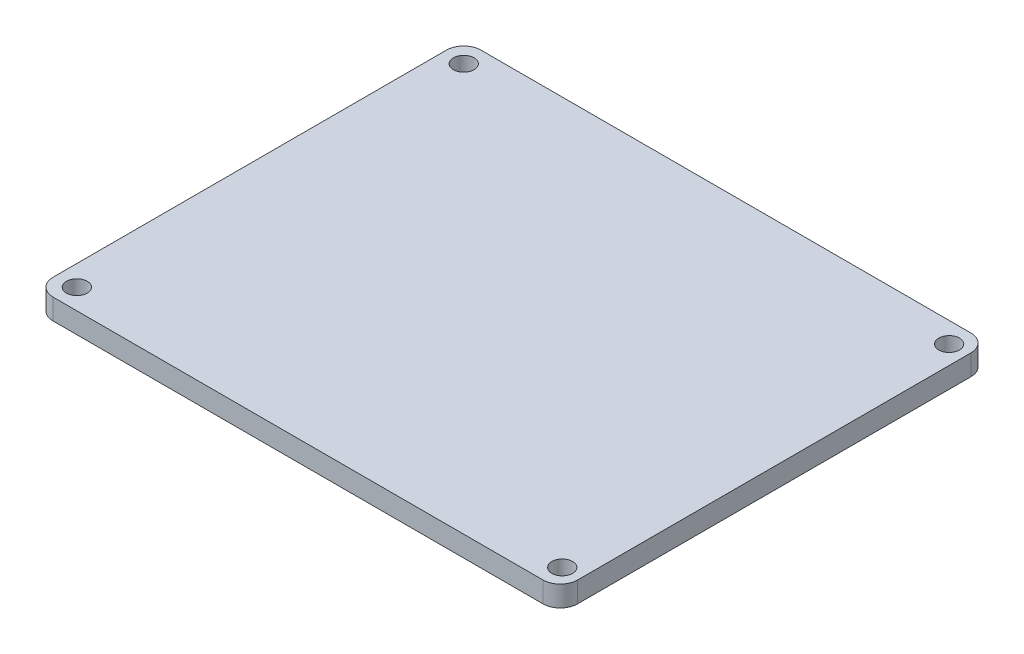
SolidWorks part; units mm, degrees
ref_plane "Alzado" through (0, 0, 0) normal (0, 0, 1) x (1, 0, 0)
ref_plane "Planta" through (0, 0, 0) normal (0, 1, 0) x (1, 0, 0)
ref_plane "Vista lateral" through (0, 0, 0) normal (1, 0, 0) x (0, 0, -1)
sketch "Croquis1" plane through (0, 0, 0) normal (0, 1, 0) x (1, 0, 0)
  line L0 (-5.9343, 0) -> (5.6485, 0) construction
  line L1 (-32.5, 25.5) -> (32.5, 25.5) construction
  line L2 (-32.5, 25.5) -> (-32.5, -25.5) construction
  line L3 (-32.5, -25.5) -> (32.5, -25.5) construction
  line L4 (32.5, 25.5) -> (32.5, -25.5) construction
  line L5 (-32.5, 25.5) -> (32.5, -25.5) construction
  line L6 (-32.5, -25.5) -> (32.5, 25.5) construction
  line L7 (0, 5.3897) -> (0, -5.0349) construction
  line L9 (-35.6429, 31) -> (35.3571, 31)
  line L10 (-38.1429, 28.5) -> (-38.1429, -28.5)
  line L11 (-35.6429, -31) -> (35.3571, -31)
  line L12 (37.8571, 28.5) -> (37.8571, -28.5)
  line L13 (-38.1429, 31) -> (37.8571, -31) construction
  line L14 (-38.1429, -31) -> (37.8571, 31) construction
  arc A4 (-38.1429, -28.5) -> (-35.6429, -31) centre (-35.6429, -28.5) ccw
  arc A5 (35.3571, -31) -> (37.8571, -28.5) centre (35.3571, -28.5) ccw
  arc A6 (35.3571, 31) -> (37.8571, 28.5) centre (35.3571, 28.5) cw
  arc A7 (-35.6429, 31) -> (-38.1429, 28.5) centre (-35.6429, 28.5) ccw
  circle A9 centre (-35.1695, 28.0342) radius 1.5
  circle A10 centre (35.1695, 28.0342) radius 1.5
  circle A11 centre (35.1695, -28.0342) radius 1.5
  circle A12 centre (-35.1695, -28.0342) radius 1.5
  point P0 (0, 0)
  point P18 (-0.1429, 0)
  dimension "D3" = 3
  dimension "D8" = 2.5
  dimension "D1" = 51
  dimension "D2" = 65
  dimension "D6" = 76
  dimension "D7" = 62
extrude "Saliente-Extruir1" add sketch "Croquis1" along normal blind 3
